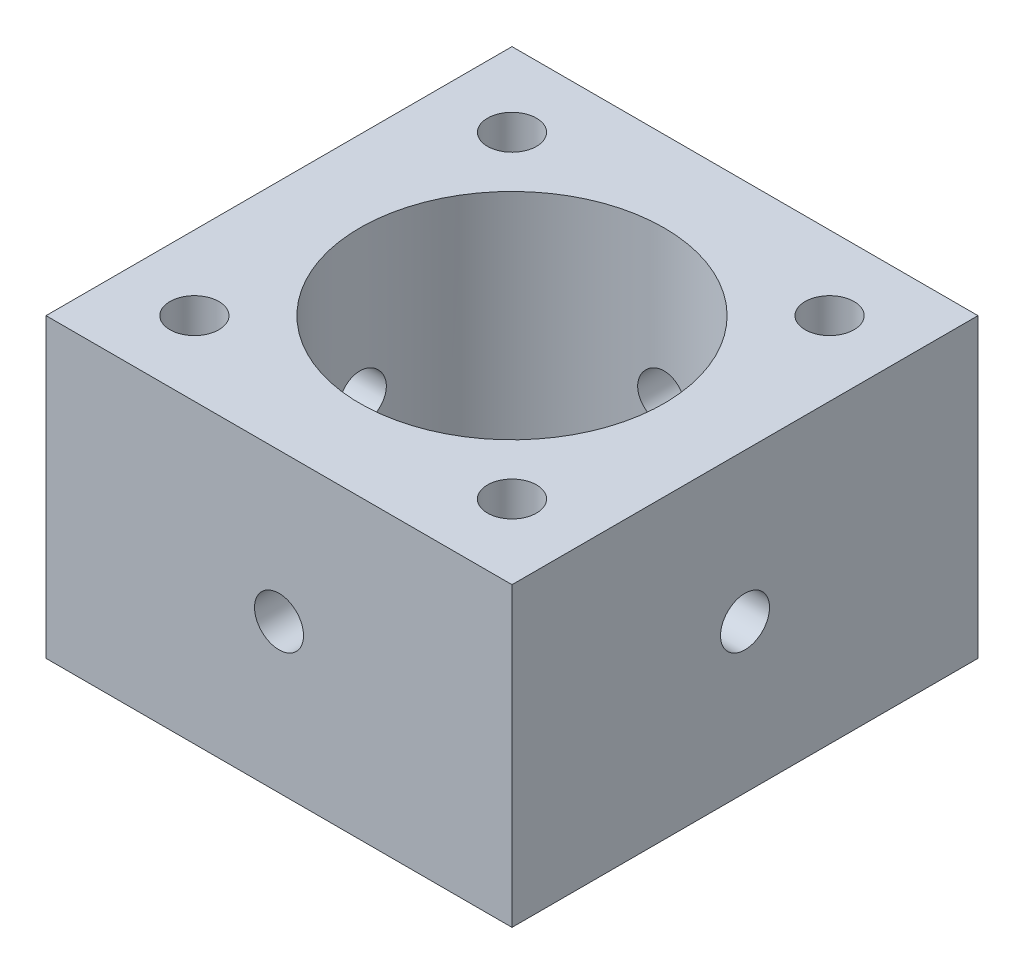
SolidWorks part; units mm, degrees
material "3003 Alloy"
ref_plane "Front Plane" through (0, 0, 0) normal (0, 0, 1) x (1, 0, 0)
ref_plane "Top Plane" through (0, 0, 0) normal (0, 1, 0) x (1, 0, 0)
ref_plane "Right Plane" through (0, 0, 0) normal (1, 0, 0) x (0, 0, -1)
sketch "Sketch1" plane through (0, 0, 0) normal (0, 1, 0) x (1, 0, 0)
  line L0 (-15.7, 0) -> (0, 0) construction
  line L1 (-15.7, 15.7) -> (15.7, 15.7)
  line L2 (-15.7, 15.7) -> (-15.7, -15.7)
  line L3 (-15.7, -15.7) -> (15.7, -15.7)
  line L4 (15.7, 15.7) -> (15.7, -15.7)
  line L5 (0, 0) -> (0, 15.7) construction
  circle A0 centre (0, 0) radius 10.25
  dimension "D3" = 20.5
  dimension "D1" = 31.4
  dimension "D2" = 31.4
extrude "Boss-Extrude1" add sketch "Sketch1" along normal blind 40
sketch "Sketch2" plane through (15.7, 0, 0) normal (1, 0, 0) x (0, 0, -1)
  line L0 (0, 40) -> (0, 0) construction
  line L1 (-15.7, 40) -> (15.7, 40) construction
  line L2 (-15.7, 0) -> (15.7, 0) construction
  line L3 (-15.7, 20) -> (15.7, 20) construction
  line L4 (-15.7, 40) -> (-15.7, 0) construction
  line L5 (15.7, 40) -> (15.7, 0) construction
  circle A0 centre (0, 30) radius 1.5
  circle A1 centre (0, 10) radius 1.5
  dimension "D1" = 3
  dimension "D2" = 20
extrude "Cut-Extrude1" cut sketch "Sketch2" against normal blind 40
hole_wizard "M4 Tapped Hole1" positions "3DSketch1" profile "Sketch3" tap size "M4" standard "DIN"
sketch3d "3DSketch1"
  line L0 (-15.7, 10, 0) -> (-10.1396, 10, 0) construction
  line L1 (-15.7, 30, 0) -> (-10.1396, 30, 0) construction
  line L2 (10.1396, 30, 0) -> (15.7, 30, 0) construction
  line L3 (10.1396, 10, 0) -> (15.7, 10, 0) construction
  point P0 (-15.7, 10, 0)
  point P4 (-15.7, 30, 0)
  point P8 (15.7, 30, 0)
  point P12 (15.7, 10, 0)
sketch "Sketch3" plane through (-15.7, 10, 0) normal (0, 1, 0) x (0, 0, 1)
  line L0 (0, 0) -> (0, 11.0914)
  line L1 (0, 11.0914) -> (1.65, 10.1)
  line L2 (1.65, 10.1) -> (1.65, 0)
  line L5 (1.65, 0) -> (0, 0)
  line L10 (0, 11.0914) -> (-1.65, 10.1) construction
  line L11 (0, -6.35) -> (0, 107.95) construction
  dimension "Tap Drill Dia." = 3.3
  dimension "Tap Drill Depth" = 10.1
  dimension "Drill Angle" = 118
cosmetic thread "Hole Thread1" parameters "D1"=8, "D2"=4
cosmetic thread "Hole Thread2" parameters "D1"=8, "D2"=4
cosmetic thread "Hole Thread3" parameters "D1"=8, "D2"=4
cosmetic thread "Hole Thread4" parameters "D1"=8, "D2"=4
sketch "Sketch5" plane through (0, 0, 15.7) normal (0, 0, 1) x (1, 0, 0)
  line L0 (0, 40) -> (0, 0) construction
  line L1 (-15.7, 40) -> (15.7, 40) construction
  line L2 (0, 20) -> (15.7, 20) construction
  line L3 (15.7, 40) -> (15.7, 0) construction
  circle A0 centre (0, 30) radius 1.5
  circle A1 centre (0, 10) radius 1.5
  dimension "D1" = 3
  dimension "D2" = 20
extrude "Cut-Extrude2" cut sketch "Sketch5" against normal blind 40
hole_wizard "M4 Tapped Hole2" positions "3DSketch2" profile "Sketch6" tap size "M4" standard "DIN"
sketch3d "3DSketch2"
  line L0 (0, 30, 10.1396) -> (0, 30, 15.7) construction
  line L1 (0, 30, -15.7) -> (0, 30, -10.25) construction
  line L2 (0, 10, 10.1396) -> (0, 10, 15.7) construction
  line L3 (0, 10, -15.7) -> (0, 10, -10.25) construction
  point P0 (0, 30, 15.7)
  point P4 (0, 30, -15.7)
  point P9 (0, 10, 15.7)
  point P13 (0, 10, -15.7)
sketch "Sketch6" plane through (0, 30, 15.7) normal (1, 0, 0) x (0, -1, 0)
  line L0 (0, 0) -> (0, 11.0914)
  line L1 (0, 11.0914) -> (1.65, 10.1)
  line L2 (1.65, 10.1) -> (1.65, 0)
  line L5 (1.65, 0) -> (0, 0)
  line L10 (0, 11.0914) -> (-1.65, 10.1) construction
  line L11 (0, -6.35) -> (0, 107.95) construction
  dimension "Tap Drill Dia." = 3.3
  dimension "Tap Drill Depth" = 10.1
  dimension "Drill Angle" = 118
cosmetic thread "Hole Thread5" parameters "D1"=8, "D2"=4
cosmetic thread "Hole Thread6" parameters "D1"=8, "D2"=4
cosmetic thread "Hole Thread11" parameters "D1"=8, "D2"=4
cosmetic thread "Hole Thread12" parameters "D1"=8, "D2"=4
sketch "Sketch8" plane through (0, 0, 0) normal (0, -1, 0) x (1, 0, 0)
  line L0 (0, -10.7) -> (0, 0) construction
  line L1 (10.7, -10.7) -> (-10.7, -10.7) construction
  line L2 (10.7, -10.7) -> (10.7, 10.7) construction
  line L3 (10.7, 10.7) -> (-10.7, 10.7) construction
  line L4 (-10.7, -10.7) -> (-10.7, 10.7) construction
  line L5 (0, 0) -> (-10.7, 0) construction
  line L6 (-15.7, 15.7) -> (15.7, 15.7) construction
  line L7 (-15.7, -15.7) -> (-15.7, 15.7) construction
  circle A0 centre (-10.7, 10.7) radius 1.5
  circle A1 centre (10.7, 10.7) radius 1.5
  circle A2 centre (10.7, -10.7) radius 1.5
  circle A3 centre (-10.7, -10.7) radius 1.5
  dimension "D1" = 3
  dimension "D2" = 5
  dimension "D3" = 5
extrude "Cut-Extrude3" cut sketch "Sketch8" against normal blind 30
hole_wizard "M4 Tapped Hole3" positions "3DSketch3" profile "Sketch9" tap size "M4" standard "DIN"
sketch3d "3DSketch3"
  line L0 (-10.7, 30, 10.7) -> (-10.7, 0, 10.7) construction
  line L1 (10.7, 30, 10.7) -> (10.7, 0, 10.7) construction
  line L2 (10.7, 30, -10.7) -> (10.7, 0, -10.7) construction
  line L3 (-10.7, 30, -10.7) -> (-10.7, 0, -10.7) construction
  point P0 (-10.7, 0, 10.7)
  point P4 (10.7, 0, 10.7)
  point P8 (10.7, 0, -10.7)
  point P12 (-10.7, 0, -10.7)
sketch "Sketch9" plane through (-10.7, 0, 10.7) normal (1, 0, 0) x (0, 0, -1)
  line L0 (0, 0) -> (0, 53.0914)
  line L1 (0, 53.0914) -> (1.65, 52.1)
  line L2 (1.65, 52.1) -> (1.65, 0)
  line L5 (1.65, 0) -> (0, 0)
  line L10 (0, 53.0914) -> (-1.65, 52.1) construction
  line L11 (0, -6.35) -> (0, 107.95) construction
  dimension "Tap Drill Dia." = 3.3
  dimension "Tap Drill Depth" = 52.1
  dimension "Drill Angle" = 118
cosmetic thread "Hole Thread7" parameters "D1"=40, "D2"=4
cosmetic thread "Hole Thread8" parameters "D1"=40, "D2"=4
cosmetic thread "Hole Thread9" parameters "D1"=40, "D2"=4
cosmetic thread "Hole Thread10" parameters "D1"=40, "D2"=4
sketch "Sketch10" plane through (0, 0, 15.7) normal (0, 0, 1) x (1, 0, 0)
  line L0 (-15.7, 40) -> (-15.7, 0) construction
  line L1 (-15.7, 20) -> (15.7, 20)
  line L2 (-15.7, 20) -> (-15.7, 40)
  line L3 (-15.7, 40) -> (15.7, 40)
  line L4 (15.7, 20) -> (15.7, 40)
extrude "Cut-Extrude4" cut sketch "Sketch10" against normal through all
